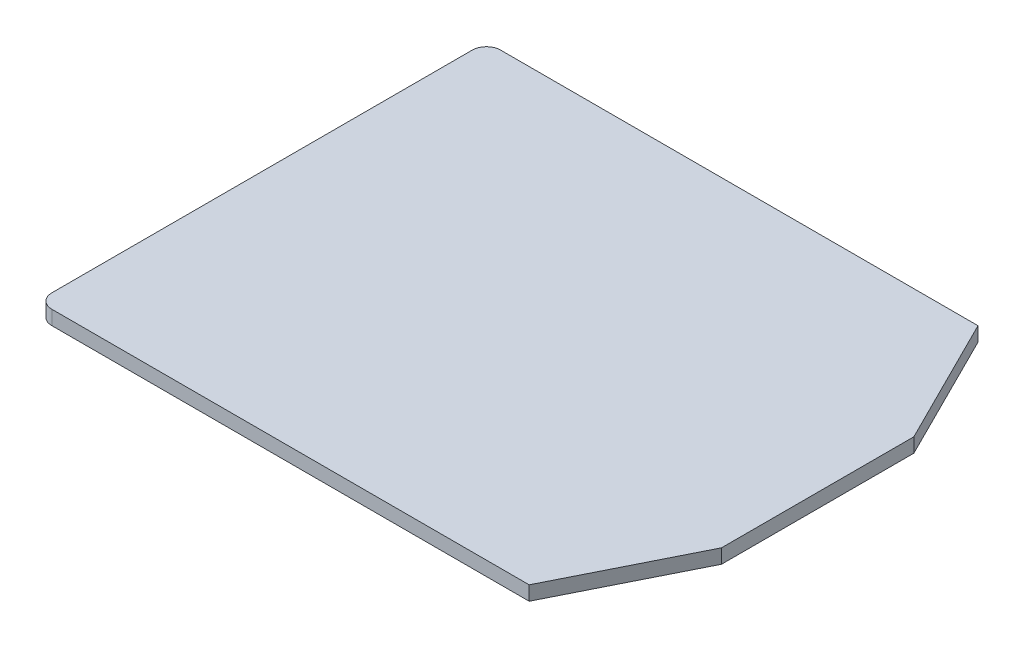
SolidWorks part; units mm, degrees
ref_plane "Alzado" through (0, 0, 0) normal (0, 0, 1) x (1, 0, 0)
ref_plane "Planta" through (0, 0, 0) normal (0, 1, 0) x (1, 0, 0)
ref_plane "Vista lateral" through (0, 0, 0) normal (1, 0, 0) x (0, 0, -1)
sketch "Croquis1" plane through (0, 0, 0) normal (0, 1, 0) x (1, 0, 0)
  line L0 (63, 0) -> (69, 0)
  line L1 (0, 0) -> (63, 0)
  line L2 (0, 0) -> (0, 63)
  line L3 (0, 63) -> (63, 63)
  line L5 (69, 0) -> (78, 18)
  line L6 (78, 18) -> (78, 45)
  line L7 (78, 45) -> (69, 63)
  line L8 (69, 63) -> (63, 63)
  dimension "D1" = 63
  dimension "D2" = 63
  dimension "D3" = 63
  dimension "D4" = 6
  dimension "D5" = 6
  dimension "D6" = 15
  dimension "D7" = 27
  dimension "D8" = 18
extrude "Saliente-Extruir1" add sketch "Croquis1" along normal blind 2
fillet "Redondeo1" radius 2 2 edges at (0, 1, -63) (0, 1, 0)
sketch "Croquis4" plane through (0, 2, 0) normal (0, 1, 0) x (1, 0, 0)
  line L0 (69, 63) -> (2, 63) construction
  line L4 (2, 0) -> (69, 0) construction
  line L5 (0, 61) -> (0, 2) construction
  line L6 (78, 18) -> (78, 45) construction
  circle A0 centre (20, 47.25) radius 3
  circle A1 centre (20, 15.75) radius 3
  circle A2 centre (58, 31.5) radius 3
  dimension "D1" = 6
  dimension "D2" = 6
  dimension "D3" = 6
  dimension "D4" = 31.5
  dimension "D5" = 20
  dimension "D6" = 15.75
  dimension "D7" = 15.75
  dimension "D8" = 20
  dimension "D9" = 20
extrude "Saliente-Extruir2" add sketch "Croquis4" against normal blind 7
fillet "Redondeo2" radius 2 3 edges at (58, -5, -28.5) (20, -5, -44.25) (20, -5, -12.75)
